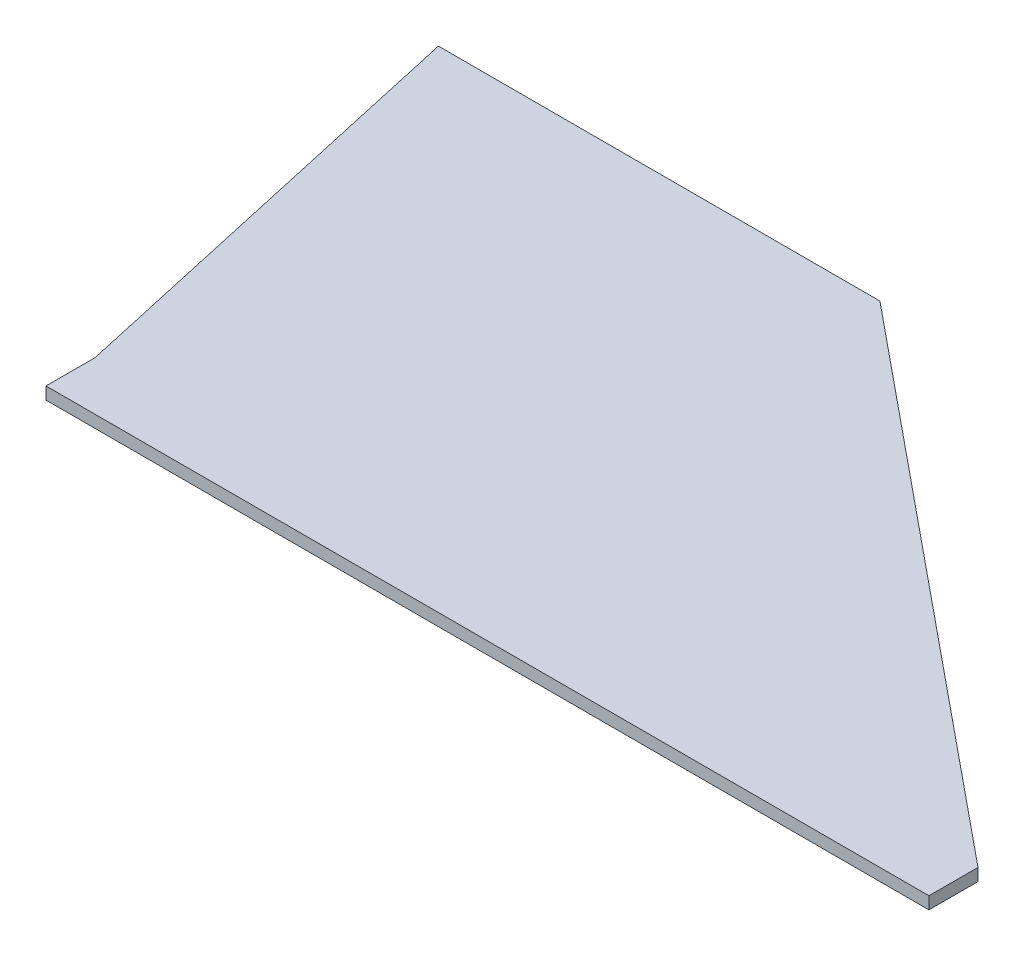
SolidWorks part; units mm, degrees
ref_plane "Front Plane" through (0, 0, 0) normal (0, 0, 1) x (1, 0, 0)
ref_plane "Top Plane" through (0, 0, 0) normal (0, 1, 0) x (1, 0, 0)
ref_plane "Right Plane" through (0, 0, 0) normal (1, 0, 0) x (0, 0, -1)
sketch "Sketch1" plane through (0, 0, 0) normal (0, 1, 0) x (1, 0, 0)
  line L0 (0, 25.4) -> (-50.8, 254)
  line L1 (0, 0) -> (457.2, 0)
  line L2 (0, 0) -> (0, 25.4)
  line L4 (457.2, 0) -> (457.2, 25.4)
  line L5 (-50.8, 254) -> (177.8, 254)
  line L6 (177.8, 254) -> (457.2, 25.4)
  point P5 (457.2, 12.7)
  dimension "D1" = 457.2
  dimension "D2" = 25.4
  dimension "D3" = 50.8
  dimension "D4" = 228.6
  dimension "D5" = 228.6
  dimension "D6" = 457.2
extrude "Boss-Extrude1" add sketch "Sketch1" along normal blind 6.35
